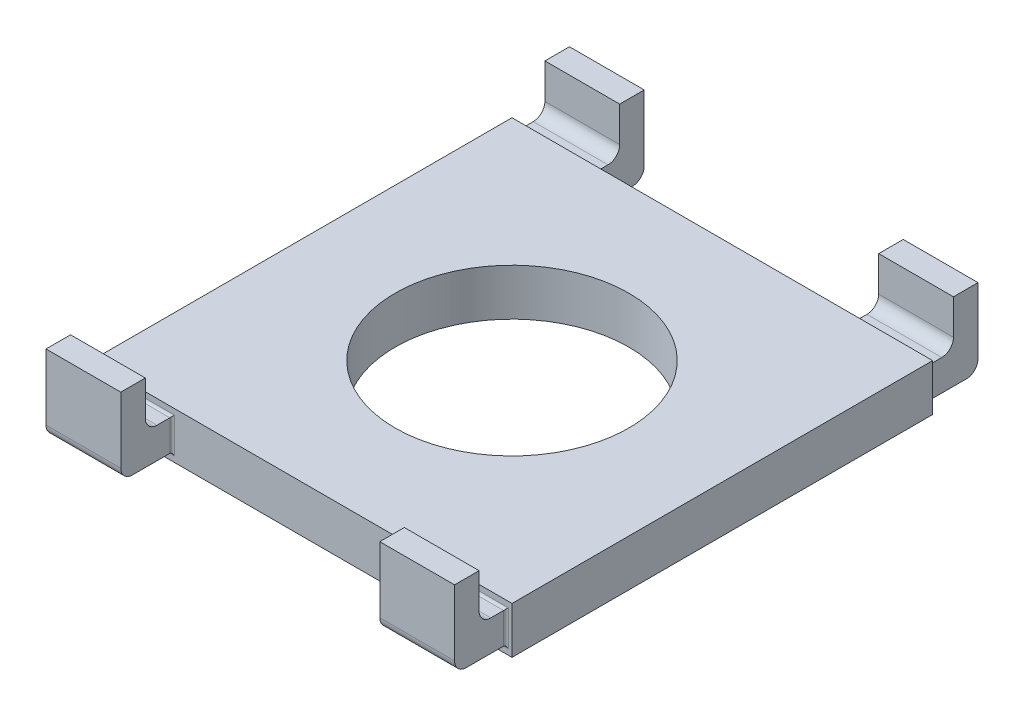
SolidWorks part; units mm, degrees
ref_plane "Front Plane" through (0, 0, 0) normal (0, 0, 1) x (1, 0, 0)
ref_plane "Top Plane" through (0, 0, 0) normal (0, 1, 0) x (1, 0, 0)
ref_plane "Right Plane" through (0, 0, 0) normal (1, 0, 0) x (0, 0, -1)
sketch "Sketch2" plane through (0, 0, 0) normal (0, 1, 0) x (1, 0, 0)
  line L1 (-22.5, 22.5) -> (22.5, 22.5)
  line L2 (-22.5, 22.5) -> (-22.5, -22.5)
  line L3 (-22.5, -22.5) -> (22.5, -22.5)
  line L4 (22.5, 22.5) -> (22.5, -22.5)
  point P0 (0, 0)
  dimension "D1" = 45
extrude "Boss-Extrude1" add sketch "Sketch2" along normal blind 5
sketch "Sketch3" plane through (0, 0, 0) normal (0, 0, 1) x (1, 0, 0)
  line L1 (-21.8536, 4.15) -> (-13.8536, 4.15)
  line L2 (-21.8536, 4.15) -> (-21.8536, 0.85)
  line L3 (-21.8536, 0.85) -> (-13.8536, 0.85)
  line L4 (-13.8536, 4.15) -> (-13.8536, 0.85)
  line L5 (-21.8536, 4.15) -> (-13.8536, 0.85) construction
  line L6 (-21.8536, 0.85) -> (-13.8536, 4.15) construction
  line L8 (0, -2.75) -> (0, 2.75) construction
  line L9 (21.8536, 4.15) -> (21.8536, 0.85)
  line L10 (21.8536, 0.85) -> (13.8536, 0.85)
  line L11 (13.8536, 4.15) -> (13.8536, 0.85)
  line L12 (21.8536, 4.15) -> (13.8536, 4.15)
  point P0 (-17.8536, 2.5)
extrude "Boss-Extrude2" add sketch "Sketch3" along normal mid plane 56
fillet "Fillet1" radius 0.25 16 edges at (-13.8536, 2.5, -22.5) (-17.8536, 4.15, -22.5) (-21.8536, 2.5, -22.5) (-17.8536, 0.85, -22.5) (17.8536, 0.85, -22.5) (13.8536, 2.5, -22.5) (21.8536, 2.5, -22.5) (17.8536, 4.15, -22.5) (21.8536, 2.5, 22.5) (17.8536, 4.15, 22.5) (17.8536, 0.85, 22.5) (13.8536, 2.5, 22.5) (-21.8536, 2.5, 22.5) (-13.8536, 2.5, 22.5) (-17.8536, 0.85, 22.5) (-17.8536, 4.15, 22.5)
sketch "Sketch4" plane through (0, 4.15, 0) normal (0, 1, 0) x (1, 0, 0)
  line L0 (-13.8536, 22.75) -> (-13.8536, 28) construction
  line L1 (-21.8536, 28) -> (-13.8536, 28)
  line L2 (-21.8536, 28) -> (-21.8536, 25.375)
  line L3 (-21.8536, 25.375) -> (-13.8536, 25.375)
  line L4 (-13.8536, 28) -> (-13.8536, 25.375)
  line L5 (21.8536, 22.75) -> (21.8536, 28) construction
  line L6 (13.8536, 28) -> (21.8536, 28)
  line L7 (13.8536, 28) -> (13.8536, 25.375)
  line L8 (13.8536, 25.375) -> (21.8536, 25.375)
  line L9 (21.8536, 28) -> (21.8536, 25.375)
  line L10 (13.8536, -28) -> (13.8536, -22.75) construction
  line L11 (21.8536, -28) -> (13.8536, -28)
  line L12 (21.8536, -28) -> (21.8536, -25.375)
  line L13 (21.8536, -25.375) -> (13.8536, -25.375)
  line L14 (13.8536, -28) -> (13.8536, -25.375)
  line L15 (-21.8536, -28) -> (-21.8536, -22.75) construction
  line L16 (-13.8536, -28) -> (-21.8536, -28)
  line L17 (-13.8536, -28) -> (-13.8536, -25.375)
  line L18 (-13.8536, -25.375) -> (-21.8536, -25.375)
  line L19 (-21.8536, -28) -> (-21.8536, -25.375)
extrude "Boss-Extrude3" add sketch "Sketch4" along normal blind 5
fillet "Fillet2" radius 1.25 8 edges at (-17.8536, 0.85, -28) (-17.8536, 0.85, 28) (17.8536, 0.85, -28) (17.8536, 0.85, 28) (17.8536, 4.15, 25.375) (-17.8536, 4.15, 25.375) (17.8536, 4.15, -25.375) (-17.8536, 4.15, -25.375)
sketch "Sketch6" plane through (0, 5, 0) normal (0, 1, 0) x (1, 0, 0)
  circle A0 centre (0, 0) radius 12.5
  dimension "D1" = 25
extrude "Cut-Extrude1" cut sketch "Sketch6" against normal blind 19
